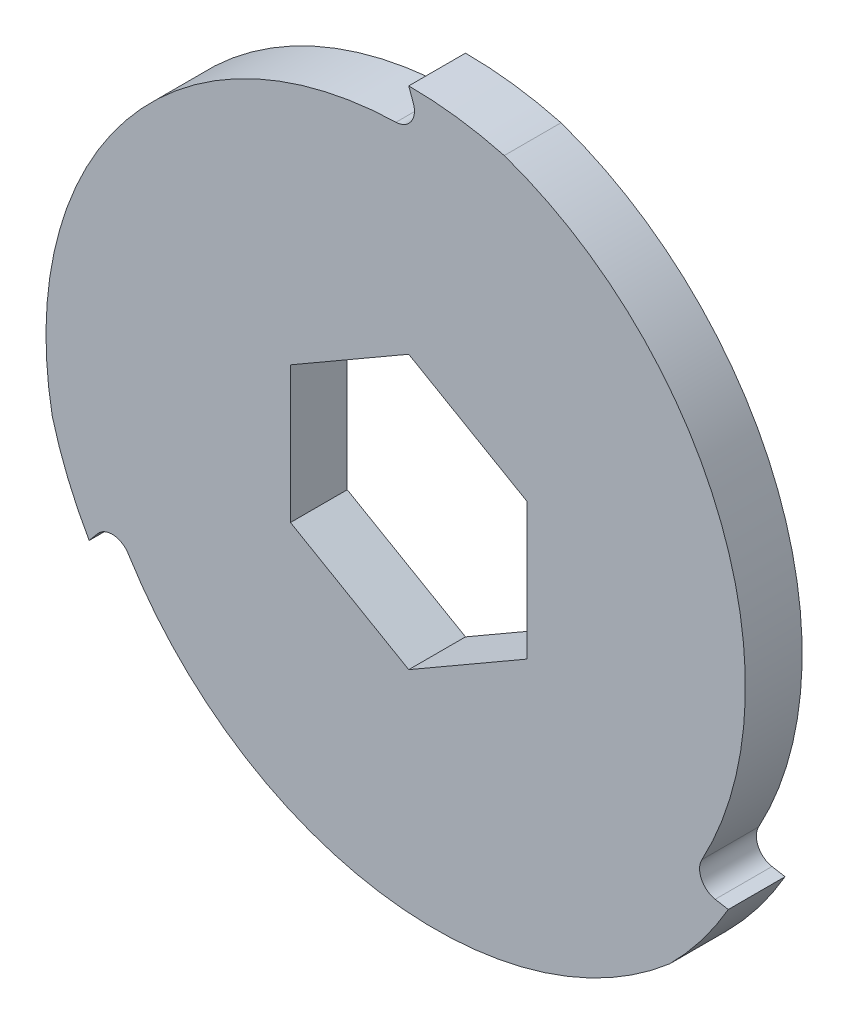
SolidWorks part; units mm, degrees
material "S45C"
ref_plane "Front Plane" through (0, 0, 0) normal (0, 0, 1) x (1, 0, 0)
ref_plane "Top Plane" through (0, 0, 0) normal (0, 1, 0) x (1, 0, 0)
ref_plane "Right Plane" through (0, 0, 0) normal (1, 0, 0) x (0, 0, -1)
sketch "Sketch1" plane through (0, 0, 0) normal (0, 0, 1) x (1, 0, 0)
  line L0 (0, 39) -> (1.4671, 34.9692)
  line L1 (0, 14.4338) -> (-12.5, 7.2169)
  line L2 (-12.5, 7.2169) -> (-12.5, -7.2169)
  line L3 (-12.5, -7.2169) -> (0, -14.4338)
  line L4 (0, -14.4338) -> (12.5, -7.2169)
  line L5 (12.5, -7.2169) -> (12.5, 7.2169)
  line L6 (12.5, 7.2169) -> (0, 14.4338)
  line L7 (0, 0) -> (0, 39) construction
  line L8 (33.775, -19.5) -> (29.5507, -18.7551)
  line L9 (-33.775, -19.5) -> (-31.0178, -16.2141)
  line L10 (0, 0) -> (10.0939, 37.6711) construction
  circle A0 centre (0, 0) radius 12.5 construction
  circle A1 centre (0, 0) radius 39
  circle A2 centre (0, 0) radius 35 construction
  arc A3 (10.0939, 37.6711) -> (29.5507, -18.7551) centre (-2.4167, 1.7896) cw
  arc A4 (27.5772, -27.5772) -> (-31.0178, -16.2141) centre (2.7582, 1.1981) cw
  arc A5 (-37.6711, -10.0939) -> (1.4671, 34.9692) centre (-0.3415, -2.9877) cw
  dimension "D1" = 25
  dimension "D2" = 78
  dimension "D7" = 38
  dimension "D4" = 20
  dimension "D6" = 15
  dimension "D3" = 4
  dimension "D5" = 3
  dimension "D8" = 3
extrude "Boss-Extrude1" add sketch "Sketch1" along normal mid plane 6 contours A5 A1 L9 A4 L8 A3 L0 L6 L5 L4 L3 L2 L1
fillet "Fillet1" radius 2 3 edges at (29.5507, -18.7551, 0) (-31.0178, -16.2141, 0) (1.4671, 34.9692, 0)
